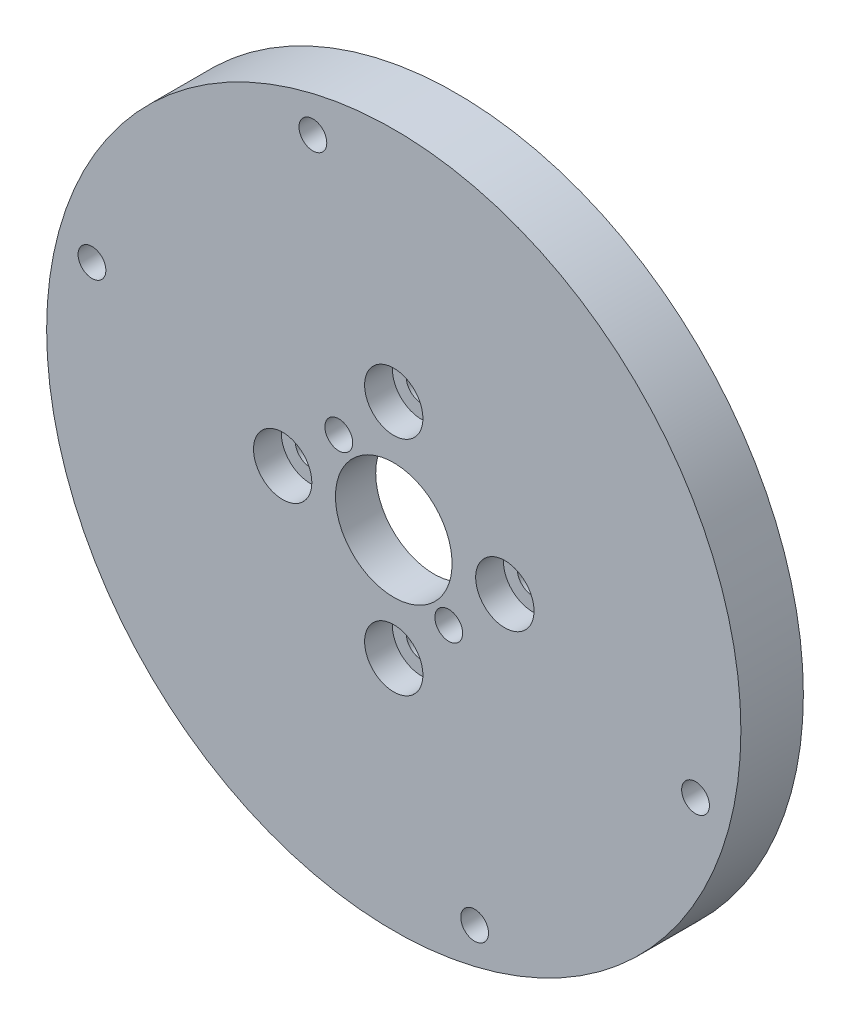
SolidWorks part; units mm, degrees
ref_plane "정면" through (0, 0, 0) normal (0, 0, 1) x (1, 0, 0)
ref_plane "윗면" through (0, 0, 0) normal (0, 1, 0) x (1, 0, 0)
ref_plane "우측면" through (0, 0, 0) normal (1, 0, 0) x (0, 0, -1)
sketch "스케치1" plane through (0, 0, 0) normal (0, 0, 1) x (1, 0, 0)
  line L0 (0, 0) -> (0, 25) construction
  line L1 (0, 0) -> (6.7175, 6.7175) construction
  line L2 (0, 0) -> (-5.8234, 21.7333) construction
  line L4 (0, 0) -> (-10.6066, 10.6066) construction
  circle A0 centre (0, 0) radius 2.3
  circle A1 centre (0, 0) radius 8 construction
  circle A2 centre (0, 0) radius 25
  circle A3 centre (0, 8) radius 1.1
  circle A4 centre (8, 0) radius 1.1
  circle A5 centre (0, -8) radius 1.1
  circle A6 centre (-8, 0) radius 1.1
  circle A7 centre (0, 0) radius 9.5 construction
  circle A8 centre (-5.8234, 21.7333) radius 1
  circle A9 centre (0, 0) radius 15 construction
  circle A10 centre (21.7333, -5.8234) radius 1
  circle A11 centre (5.8234, -21.7333) radius 1
  circle A12 centre (-21.7333, 5.8234) radius 1
  point P17 (0, 0)
  point P25 (0, 0)
  point P28 (0, 0)
  dimension "D1" = 4.6
  dimension "D2" = 16
  dimension "D3" = 50
  dimension "D4" = 2.2
  dimension "D6" = 19
  dimension "D8" = 22.5
  dimension "D9" = 2
  dimension "D7" = 45
  dimension "D10" = 60
  dimension "D5" = 4
extrude "보스-돌출1" add sketch "스케치1" along normal blind 4.5
sketch "스케치2" plane through (0, 0, 4.5) normal (0, 0, 1) x (1, 0, 0)
  circle A0 centre (0, 8) radius 2.1
  circle A1 centre (8, 0) radius 2.1
  circle A2 centre (0, -8) radius 2.1
  circle A3 centre (-8, 0) radius 2.1
  point P12 (0, 0)
  dimension "D2" = 4.2
  dimension "D1" = 4
extrude "컷-돌출1" cut sketch "스케치2" against normal blind 2
sketch "스케치10" plane through (0, 0, 0) normal (0, 0, -1) x (-1, 0, 0)
  circle A0 centre (0, 0) radius 10
  dimension "D1" = 20
extrude "컷-돌출7" cut sketch "스케치10" against normal blind 1.6
sketch "스케치9" plane through (0, 0, 1.6) normal (0, 0, -1) x (-1, 0, 0)
  circle A0 centre (0, 0) radius 4.2
  dimension "D1" = 8.4
extrude "컷-돌출5" cut sketch "스케치9" against normal through all
sketch "스케치6" plane through (0, 0, 4.5) normal (0, 0, 1) x (1, 0, 0)
  line L0 (0, 0) -> (-3.9598, 3.9598) construction
  line L1 (0, 0) -> (3.9598, -3.9598) construction
  line L2 (0, 0) -> (4.415, 0) construction
  circle A0 centre (-3.9598, 3.9598) radius 1
  circle A1 centre (3.9598, -3.9598) radius 1
  dimension "D2" = 2
  dimension "D4" = 2
  dimension "D1" = 5.6
  dimension "D3" = 5.6
  dimension "D5" = 45
extrude "컷-돌출6" cut sketch "스케치6" against normal blind 2
